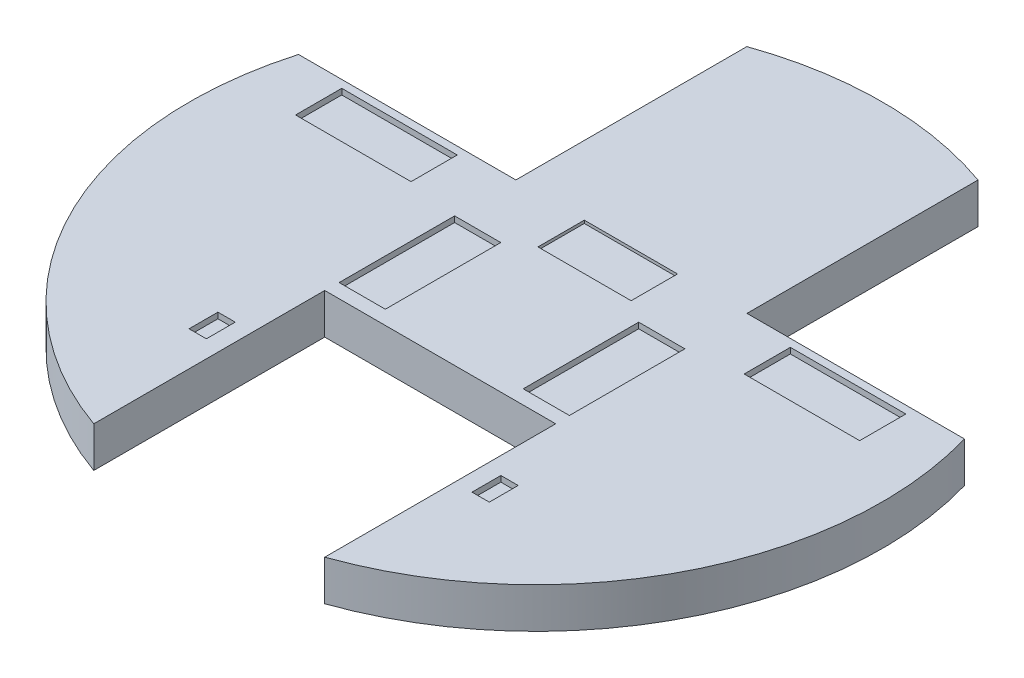
SolidWorks part; units mm, degrees
material "Maple"
ref_plane "Front Plane" through (0, 0, 0) normal (0, 0, 1) x (1, 0, 0)
ref_plane "Top Plane" through (0, 0, 0) normal (0, 1, 0) x (1, 0, 0)
ref_plane "Right Plane" through (0, 0, 0) normal (1, 0, 0) x (0, 0, -1)
sketch "Sketch1" plane through (0, 0, 0) normal (0, 1, 0) x (1, 0, 0)
  line L0 (0, -152.4) -> (0, -38.1) construction
  line L1 (50.8, -42.0841) -> (-50.8, -42.0841)
  line L2 (-50.8, -42.0841) -> (-50.8, -143.6841)
  line L3 (50.8, -42.0841) -> (50.8, -143.6841)
  line L4 (0, 152.4) -> (0, -38.1) construction
  line L5 (50.8, 143.6841) -> (50.8, 42.0605)
  line L6 (50.8, 42.0605) -> (146.481, 42.0605)
  line L7 (-50.8666, 143.6605) -> (-50.8666, 42.0605)
  line L8 (-50.8666, 42.0605) -> (-146.481, 42.0605)
  line L9 (-50.8666, 42.0605) -> (50.8, 42.0605) construction
  arc A0 (-146.481, 42.0605) -> (-50.8, -143.6841) centre (0, 0) ccw
  arc A1 (50.8, 143.6841) -> (-50.8666, 143.6605) centre (0, 0) ccw
  arc A2 (50.8, -143.6841) -> (146.481, 42.0605) centre (0, 0) ccw
  point P8 (0, -38.1)
  dimension "D1" = 304.8
  dimension "D2" = 101.6
  dimension "D3" = 101.6
  dimension "D4" = 101.6
extrude "Boss-Extrude1" add sketch "Sketch1" along normal blind 17.78
sketch "Sketch2" plane through (0, 17.78, 0) normal (0, 1, 0) x (1, 0, 0)
  line L0 (-50.8666, 42.0605) -> (50.8, 42.0605) construction
  line L1 (50.8, 42.0605) -> (50.8, 143.6841) construction
  line L2 (0, -42.0841) -> (-0.0353, 152.4) construction
  line L3 (-50.8, -42.0841) -> (50.8, -42.0841) construction
  line L5 (-20.5, 41.7986) -> (20.5, 41.7986)
  line L6 (-20.5, 41.7986) -> (-20.5, 21.3986)
  line L7 (-20.5, 21.3986) -> (20.5, 21.3986)
  line L8 (20.5, 41.7986) -> (20.5, 21.3986)
  line L9 (-20.5, 41.7986) -> (20.5, 21.3986) construction
  line L10 (-20.5, 21.3986) -> (20.5, 41.7986) construction
  arc A0 (50.8, 143.6841) -> (-50.8666, 143.6605) centre (0, 0) ccw construction
  dimension "D1" = 41
  dimension "D2" = 20.4
extrude "Cut-Extrude1" cut sketch "Sketch2" against normal blind 1.27
sketch "Sketch3" plane through (0, 17.78, 0) normal (0, 1, 0) x (1, 0, 0)
  line L0 (0, -42.0841) -> (0, -143.6841) construction
  line L1 (-50.8, -42.0841) -> (50.8, -42.0841) construction
  line L2 (-50.8, -80.1841) -> (50.8, -80.1841) construction
  line L3 (0, -9.779) -> (0, 9.779) construction
  line L4 (-66.04, -73.8341) -> (-58.42, -73.8341)
  line L5 (50.8, -80.1841) -> (58.42, -80.1841) construction
  line L6 (-50.8, -80.1841) -> (-58.42, -80.1841) construction
  line L7 (-58.42, -80.1841) -> (-62.23, -80.1841) construction
  line L8 (-66.04, -73.8341) -> (-66.04, -86.5341)
  line L9 (-66.04, -86.5341) -> (-58.42, -86.5341)
  line L10 (-58.42, -73.8341) -> (-58.42, -86.5341)
  line L11 (-66.04, -73.8341) -> (-58.42, -86.5341) construction
  line L12 (-66.04, -86.5341) -> (-58.42, -73.8341) construction
  line L13 (66.04, -86.5341) -> (58.42, -86.5341)
  line L14 (58.42, -73.8341) -> (58.42, -86.5341)
  line L15 (66.04, -73.8341) -> (58.42, -73.8341)
  line L16 (66.04, -73.8341) -> (66.04, -86.5341)
  dimension "D1" = 7.62
  dimension "D2" = 7.62
  dimension "D3" = 38.1
  dimension "D4" = 3.81
  dimension "D5" = 7.62
  dimension "D6" = 12.7
extrude "Cut-Extrude2" cut sketch "Sketch3" against normal blind 2.54
sketch "Sketch4" plane through (0, 17.78, 0) normal (0, 1, 0) x (1, 0, 0)
  line L0 (-151.6637, 14.9624) -> (151.6637, 14.9624) construction
  line L1 (-98.6738, 42.0605) -> (-98.6738, 14.9624) construction
  line L2 (-50.8666, 42.0605) -> (-146.481, 42.0605) construction
  line L3 (0, -9.779) -> (0, 9.779) construction
  line L4 (-124.0738, 38.6715) -> (-73.2738, 38.6715)
  line L5 (-124.0738, 38.6715) -> (-124.0738, 18.3515)
  line L6 (-124.0738, 18.3515) -> (-73.2738, 18.3515)
  line L7 (-73.2738, 38.6715) -> (-73.2738, 18.3515)
  line L8 (-124.0738, 38.6715) -> (-73.2738, 18.3515) construction
  line L9 (-124.0738, 18.3515) -> (-73.2738, 38.6715) construction
  line L10 (124.0738, 18.3515) -> (73.2738, 18.3515)
  line L11 (73.2738, 38.6715) -> (73.2738, 18.3515)
  line L12 (124.0738, 38.6715) -> (73.2738, 38.6715)
  line L13 (124.0738, 38.6715) -> (124.0738, 18.3515)
  line L14 (-40.4854, 28.8266) -> (-40.4854, -49.8343) construction
  line L15 (-50.6454, 14.8962) -> (-30.3254, 14.8962)
  line L16 (-50.6454, 14.8962) -> (-50.6454, -35.9038)
  line L17 (-50.6454, -35.9038) -> (-30.3254, -35.9038)
  line L18 (-30.3254, 14.8962) -> (-30.3254, -35.9038)
  line L19 (-50.6454, 14.8962) -> (-30.3254, -35.9038) construction
  line L20 (-50.6454, -35.9038) -> (-30.3254, 14.8962) construction
  line L21 (40.4856, 28.0759) -> (40.4856, -49.0836) construction
  line L22 (30.3256, 14.8962) -> (50.6456, 14.8962)
  line L23 (30.3256, 14.8962) -> (30.3256, -35.9038)
  line L24 (30.3256, -35.9038) -> (50.6456, -35.9038)
  line L25 (50.6456, 14.8962) -> (50.6456, -35.9038)
  line L26 (30.3256, 14.8962) -> (50.6456, -35.9038) construction
  line L27 (30.3256, -35.9038) -> (50.6456, 14.8962) construction
  line L28 (-50.8666, 42.0605) -> (-50.8, -42.0841) construction
  line L29 (50.8, 42.0605) -> (50.8, -42.0841) construction
  arc A0 (-146.481, 42.0605) -> (-50.8, -143.6841) centre (0, 0) ccw construction
  arc A1 (50.8, -143.6841) -> (146.481, 42.0605) centre (0, 0) ccw construction
  point P12 (-98.6738, 28.5115)
  point P25 (-40.4854, -10.5038)
  point P32 (40.4856, -10.5038)
  point P45 (40.4856, -14.4836)
  point P46 (-40.4854, -10.5038)
  point P47 (40.4856, -10.5038)
  dimension "D1" = 50.8
  dimension "D2" = 20.32
  dimension "D3" = 20.32
  dimension "D4" = 50.8
  dimension "D5" = 20.32
  dimension "D6" = 50.8
extrude "Cut-Extrude3" cut sketch "Sketch4" against normal blind 2.54
